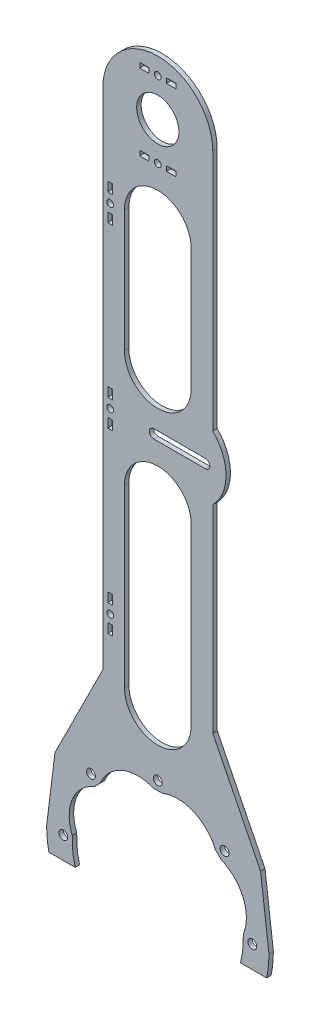
SolidWorks part; units mm, degrees
ref_plane "前视基准面" through (0, 0, 0) normal (0, 0, 1) x (1, 0, 0)
ref_plane "上视基准面" through (0, 0, 0) normal (0, 1, 0) x (1, 0, 0)
ref_plane "右视基准面" through (0, 0, 0) normal (1, 0, 0) x (0, 0, -1)
sketch "草图1" plane through (0, 0, 0) normal (0, 0, 1) x (1, 0, 0)
  line L0 (0, -125) -> (0, 175) construction
  line L3 (37.1881, -134.9645) -> (48.997, -134.9645)
  line L4 (0, -125) -> (-38.5, -125) construction
  line L5 (0, -125) -> (42.5, -125) construction
  line L6 (-37.1881, -134.9645) -> (-48.997, -134.9645)
  line L11 (-24.7418, 0) -> (-24.7418, -51.7398)
  line L12 (-24.7418, 0) -> (-24.7418, 175)
  line L14 (0, 175) -> (3.9, 175) construction
  line L17 (-3.9, 157.8791) -> (3.9, 157.8791) construction
  line L22 (-3.9, 191.0209) -> (-8.1, 193.2209) construction
  line L23 (24.7418, 0) -> (24.7418, -51.7398)
  line L24 (-3.9, 156.7791) -> (-8.1, 158.9791) construction
  line L33 (46.25, -94.7415) -> (50, -125)
  line L34 (21.4147, 51.6631) -> (-1.8098, 51.6631) construction
  line L37 (3.9, 193.2209) -> (8.1, 193.2209)
  line L38 (3.9, 193.2209) -> (3.9, 191.0209)
  line L39 (3.9, 191.0209) -> (8.1, 191.0209)
  line L40 (8.1, 193.2209) -> (8.1, 191.0209)
  line L41 (3.9, 193.2209) -> (8.1, 191.0209) construction
  line L42 (3.9, 191.0209) -> (8.1, 193.2209) construction
  line L43 (-46.25, -94.7415) -> (-50, -125)
  line L44 (24.7418, -51.7398) -> (46.25, -94.7415)
  line L45 (-24.7418, -51.7398) -> (-46.25, -94.7415)
  line L46 (3.9, 158.9791) -> (8.1, 156.7791) construction
  line L47 (-42.5, -123) -> (0, -125) construction
  line L52 (21.4147, 49.6631) -> (-1.8098, 49.6631)
  line L53 (24.7418, 0) -> (24.7418, 37.3055)
  line L54 (0, -125) -> (-42.5, -127) construction
  line L55 (0, -125) -> (-31.3981, -96.4272) construction
  line L56 (0, -125) -> (-28.6049, -93.5674) construction
  line L57 (-30.052, -94.948) -> (0, -125) construction
  line L58 (-3.9, 193.2209) -> (-8.1, 191.0209) construction
  line L59 (-8.1, 193.2209) -> (-8.1, 191.0209)
  line L60 (-3.9, 191.0209) -> (-8.1, 191.0209)
  line L61 (-3.9, 193.2209) -> (-3.9, 191.0209)
  line L62 (-3.9, 193.2209) -> (-8.1, 193.2209)
  line L63 (-3.9, 192.1209) -> (3.9, 192.1209) construction
  line L64 (-21.3921, -28.3354) -> (-21.3921, 51.6646) construction
  line L69 (-21.3921, 51.6646) -> (-21.3921, 131.6646) construction
  line L70 (-20.2921, 47.7646) -> (-22.4921, 43.5646) construction
  line L71 (-22.4921, 55.5646) -> (-22.4921, 59.7646)
  line L76 (-22.4921, 55.5646) -> (-20.2921, 55.5646)
  line L77 (24.7418, 175) -> (24.7418, 66.0208)
  line L78 (21.4147, 53.6631) -> (-1.8098, 53.6631)
  line L79 (3.9, 156.7791) -> (8.1, 158.9791) construction
  line L80 (-3.9, 158.9791) -> (-8.1, 156.7791) construction
  line L81 (-3.9, 156.7791) -> (-8.1, 156.7791)
  line L82 (-3.9, 156.7791) -> (-3.9, 158.9791)
  line L83 (-3.9, 158.9791) -> (-8.1, 158.9791)
  line L84 (-8.1, 156.7791) -> (-8.1, 158.9791)
  line L85 (8.1, 156.7791) -> (8.1, 158.9791)
  line L86 (3.9, 158.9791) -> (8.1, 158.9791)
  line L87 (3.9, 156.7791) -> (3.9, 158.9791)
  line L88 (3.9, 156.7791) -> (8.1, 156.7791)
  line L89 (0, -53.7654) -> (0, 25) construction
  line L90 (-15, -53.7654) -> (-15, 25)
  line L91 (15, -53.7654) -> (15, 25)
  line L92 (-20.2921, -32.2354) -> (-22.4921, -36.4354) construction
  line L93 (-22.4921, -24.4354) -> (-22.4921, -20.2354)
  line L94 (-22.4921, -24.4354) -> (-20.2921, -24.4354)
  line L95 (-20.2921, -24.4354) -> (-20.2921, -20.2354)
  line L96 (-22.4921, -20.2354) -> (-20.2921, -20.2354)
  line L97 (-22.4921, -24.4354) -> (-20.2921, -20.2354) construction
  line L98 (-20.2921, -24.4354) -> (-22.4921, -20.2354) construction
  line L99 (-22.4921, -32.2354) -> (-20.2921, -36.4354) construction
  line L100 (-22.4921, -36.4354) -> (-20.2921, -36.4354)
  line L101 (-20.2921, -32.2354) -> (-20.2921, -36.4354)
  line L102 (-22.4921, -32.2354) -> (-20.2921, -32.2354)
  line L103 (-22.4921, -32.2354) -> (-22.4921, -36.4354)
  line L104 (-21.3921, -32.2354) -> (-21.3921, -24.4354) construction
  line L105 (-20.2921, 55.5646) -> (-20.2921, 59.7646)
  line L106 (-22.4921, 59.7646) -> (-20.2921, 59.7646)
  line L107 (-22.4921, 55.5646) -> (-20.2921, 59.7646) construction
  line L108 (-20.2921, 55.5646) -> (-22.4921, 59.7646) construction
  line L109 (-22.4921, 47.7646) -> (-20.2921, 43.5646) construction
  line L110 (-22.4921, 43.5646) -> (-20.2921, 43.5646)
  line L111 (-20.2921, 47.7646) -> (-20.2921, 43.5646)
  line L120 (0, 77.4351) -> (0, 132.4351) construction
  line L121 (-15, 77.4351) -> (-15, 132.4351)
  line L122 (15, 77.4351) -> (15, 132.4351)
  line L123 (-22.4921, 47.7646) -> (-20.2921, 47.7646)
  line L124 (-22.4921, 47.7646) -> (-22.4921, 43.5646)
  line L125 (-21.3921, 47.7646) -> (-21.3921, 55.5646) construction
  line L126 (-20.2921, 127.7646) -> (-22.4921, 123.5646) construction
  line L127 (-22.4921, 135.5646) -> (-22.4921, 139.7646)
  line L128 (-22.4921, 135.5646) -> (-20.2921, 135.5646)
  line L129 (-20.2921, 135.5646) -> (-20.2921, 139.7646)
  line L130 (-22.4921, 139.7646) -> (-20.2921, 139.7646)
  line L131 (-22.4921, 135.5646) -> (-20.2921, 139.7646) construction
  line L132 (-20.2921, 135.5646) -> (-22.4921, 139.7646) construction
  line L133 (-22.4921, 127.7646) -> (-20.2921, 123.5646) construction
  line L134 (-22.4921, 123.5646) -> (-20.2921, 123.5646)
  line L135 (-20.2921, 127.7646) -> (-20.2921, 123.5646)
  line L136 (-22.4921, 127.7646) -> (-20.2921, 127.7646)
  line L137 (-22.4921, 127.7646) -> (-22.4921, 123.5646)
  line L138 (-21.3921, 127.7646) -> (-21.3921, 135.5646) construction
  arc A0 (-15, -53.7654) -> (15, -53.7654) centre (0, -53.7654) ccw
  arc A1 (15, 25) -> (-15, 25) centre (0, 25) ccw
  circle A13 centre (0, -125) radius 42.5 construction
  circle A14 centre (0, -167.5) radius 2 construction
  circle A15 centre (-30.052, -155.052) radius 2 construction
  circle A16 centre (-42.5, -125) radius 2
  circle A17 centre (-30.052, -94.948) radius 2
  circle A18 centre (0, -82.5) radius 2
  circle A19 centre (30.052, -94.948) radius 2
  circle A20 centre (42.5, -125) radius 2
  circle A21 centre (30.052, -155.052) radius 2 construction
  arc A24 (-50, -125) -> (50, -125) centre (0, -125) ccw construction
  arc A26 (-37.1881, -134.9645) -> (37.1881, -134.9645) centre (0, -125) cw construction
  arc A27 (-50, -125) -> (-48.2963, -137.941) centre (0, -125) ccw construction
  circle A31 centre (0, 175) radius 24.7418 construction
  arc A32 (-24.7418, 175) -> (24.7418, 175) centre (0, 175) cw
  circle A33 centre (0, 175) radius 9.5
  circle A43 centre (0, 175) radius 35.5 construction
  arc A48 (-38.4574, -123.1902) -> (-28.4746, -99.0877) centre (-21.4147, -116.1304) cw
  arc A49 (-1.8098, -86.5426) -> (-25.9123, -96.5254) centre (-8.8696, -103.5853) ccw
  arc A50 (1.8098, -86.5426) -> (25.9123, -96.5254) centre (8.8696, -103.5853) cw
  arc A51 (38.4574, -123.1902) -> (28.4746, -99.0877) centre (21.4147, -116.1304) ccw
  arc A52 (-38.4574, -126.8098) -> (-38.4574, -123.1902) centre (0, -125) cw
  arc A53 (-28.4746, -99.0877) -> (-25.9123, -96.5254) centre (0, -125) cw
  arc A54 (-1.8098, -86.5426) -> (1.8098, -86.5426) centre (0, -125) cw
  arc A55 (25.9123, -96.5254) -> (28.4746, -99.0877) centre (0, -125) cw
  arc A56 (38.4574, -123.1902) -> (37.1881, -134.9645) centre (0, -125) cw
  arc A57 (-38.4574, -126.8098) -> (-37.1881, -134.9645) centre (0, -125) ccw
  circle A58 centre (0, 192.1209) radius 1.5
  arc A60 (50, -125) -> (48.997, -134.9645) centre (0, -125) cw
  arc A61 (-50, -125) -> (-48.997, -134.9645) centre (0, -125) ccw
  arc A65 (21.4147, 49.6631) -> (21.4147, 53.6631) centre (21.4147, 51.6631) ccw
  arc A66 (-1.8098, 53.6631) -> (-1.8098, 49.6631) centre (-1.8098, 51.6631) ccw
  arc A68 (24.7418, 66.0208) -> (24.7418, 37.3055) centre (10.3841, 51.6631) cw
  circle A69 centre (0, 157.8791) radius 1.5
  circle A70 centre (-21.3921, -28.3354) radius 1.5
  arc A72 (-15, 77.4351) -> (15, 77.4351) centre (0, 77.4351) ccw
  arc A73 (15, 132.4351) -> (-15, 132.4351) centre (0, 132.4351) ccw
  circle A74 centre (-21.3921, 51.6646) radius 1.5
  circle A75 centre (-21.3921, 131.6646) radius 1.5
  point P2 (0, -14.3827)
  point P18 (-21.3921, 51.6646)
  point P56 (6, 192.1209)
  point P70 (-6, 157.8791)
  point P71 (6, 157.8791)
  point P72 (-21.3921, -28.3354)
  point P77 (-21.3921, -22.3354)
  point P85 (-21.3921, -34.3354)
  point P91 (9.8025, 51.6631)
  point P118 (-6, 192.1209)
  point P126 (-21.3921, 57.6646)
  point P133 (-21.3921, 45.6646)
  point P144 (-21.3921, 131.6646)
  point P147 (-21.3921, 137.6646)
  point P154 (-21.3921, 125.6646)
  point P161 (0, 104.9351)
  dimension "D1" = 8
  dimension "D4" = 71
extrude "凸台-拉伸1" add sketch "草图1" along normal blind 2
